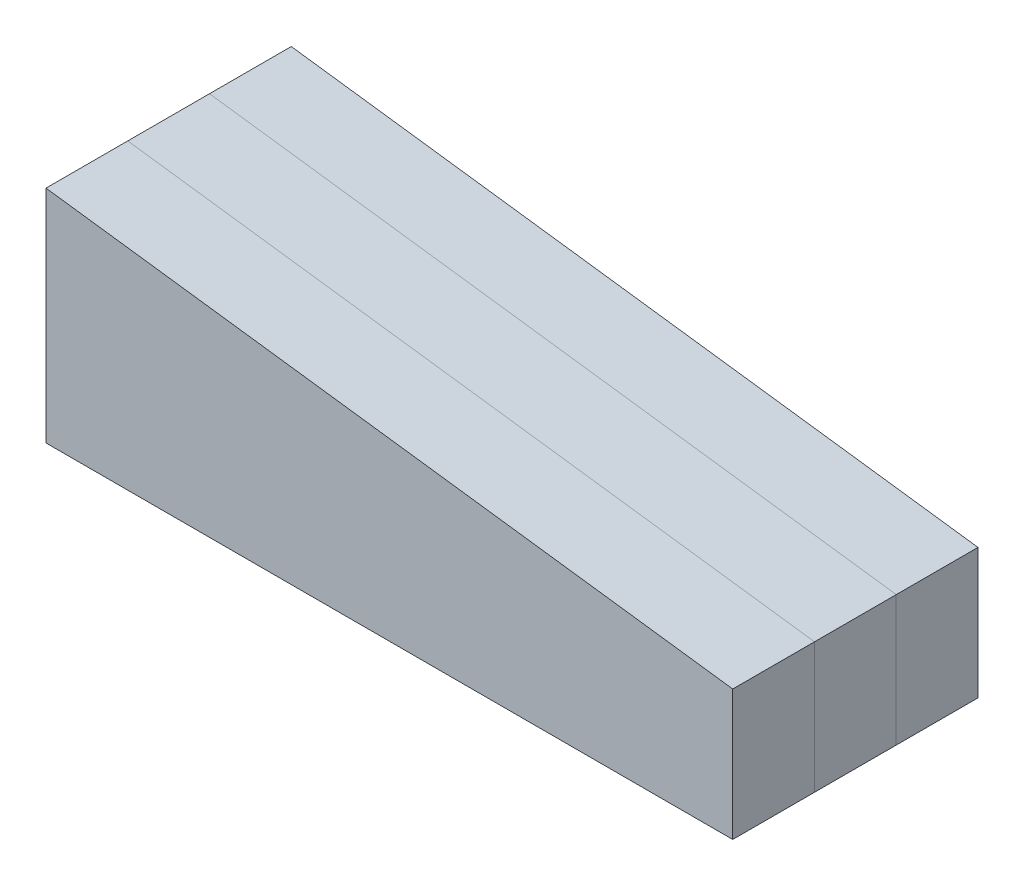
SolidWorks part; units mm, degrees
ref_plane "Front" through (0, 0, 0) normal (0, 0, 1) x (1, 0, 0)
ref_plane "Top" through (0, 0, 0) normal (0, 1, 0) x (1, 0, 0)
ref_plane "Right" through (0, 0, 0) normal (1, 0, 0) x (0, 0, -1)
sketch "Sketch1" plane through (0, 0, 0) normal (0, 0, 1) x (1, 0, 0)
  line L0 (0, 0) -> (0, 28.575)
  line L1 (0, 28.575) -> (88.9, 16.8711)
  line L2 (88.9, 16.8711) -> (88.9, 0)
  line L3 (88.9, 0) -> (0, 0)
  dimension "D1" = 88.9
  dimension "D2" = 28.575
  dimension "D4" = 7.5
extrude "Boss-Extrude1" add sketch "Sketch1" along normal mid plane 10.5833
sketch "Sketch2" plane through (0, 0, 5.2917) normal (0, 0, 1) x (1, 0, 0)
  line L8 (88.9, 16.8711) -> (0, 28.575)
  line L9 (0, 28.575) -> (0, 0)
  line L10 (0, 0) -> (88.9, 0)
  line L11 (88.9, 0) -> (88.9, 16.8711)
  line L12 (88.9, 16.8711) -> (0, 28.575)
  line L13 (0, 28.575) -> (0, 0)
  line L14 (0, 0) -> (88.9, 0)
  line L15 (88.9, 0) -> (88.9, 16.8711)
  dimension "D1" = 0
extrude "Boss-Extrude2" add sketch "Sketch2" along normal blind 10.5833 separate body
sketch "Sketch3" plane through (0, 0, 15.875) normal (0, 0, 1) x (1, 0, 0)
  line L4 (88.9, 0) -> (88.9, 16.8711)
  line L5 (88.9, 16.8711) -> (0, 28.575)
  line L6 (0, 28.575) -> (0, 0)
  line L7 (0, 0) -> (88.9, 0)
  line L8 (88.9, 0) -> (88.9, 16.8711)
  line L9 (88.9, 16.8711) -> (0, 28.575)
  line L10 (0, 28.575) -> (0, 0)
  line L11 (0, 0) -> (88.9, 0)
  dimension "D1" = 0
extrude "Boss-Extrude3" add sketch "Sketch3" along normal blind 10.5833 separate body
